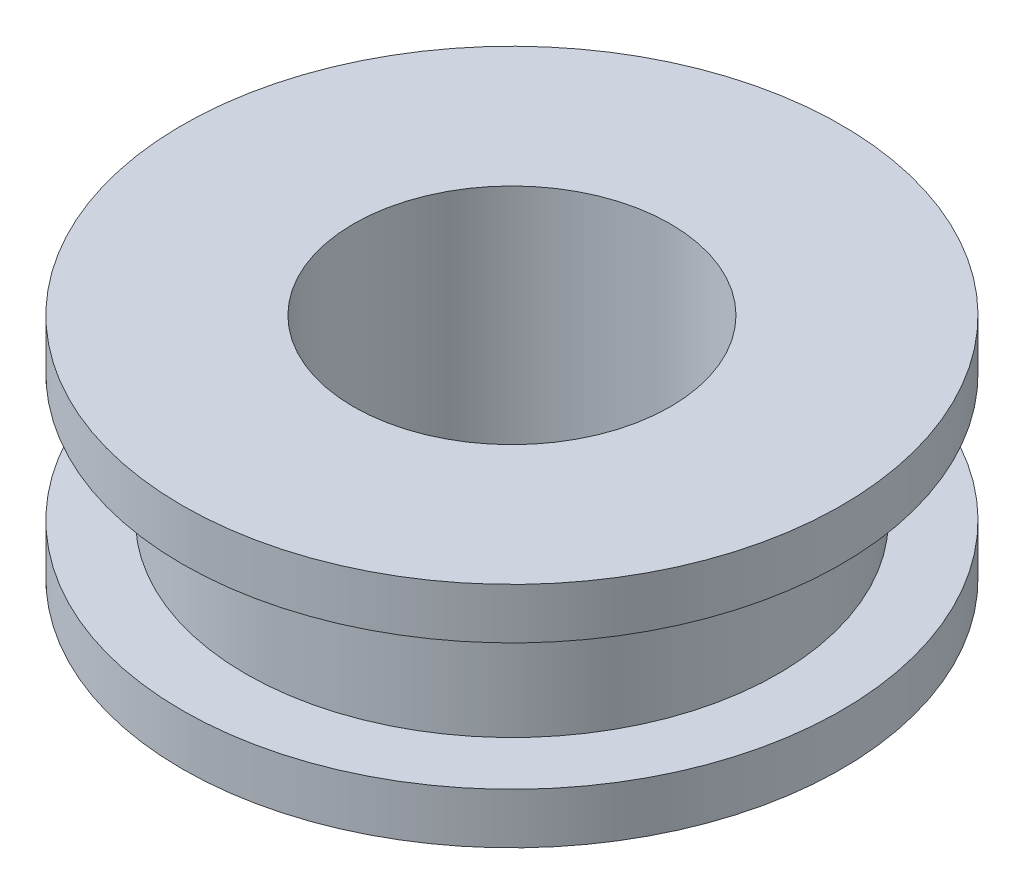
SolidWorks part; units mm, degrees
ref_plane "Front Plane" through (0, 0, 0) normal (0, 0, 1) x (1, 0, 0)
ref_plane "Top Plane" through (0, 0, 0) normal (0, 1, 0) x (1, 0, 0)
ref_plane "Right Plane" through (0, 0, 0) normal (1, 0, 0) x (0, 0, -1)
sketch "Sketch1" plane through (0, 0, 0) normal (0, 0, 1) x (1, 0, 0)
  line L0 (0, 44.3946) -> (0, -64.9116) construction
  line L1 (0, 18) -> (52, 18)
  line L2 (52, 18) -> (52, 10)
  line L3 (52, 10) -> (42, 10)
  line L4 (42, 10) -> (42, -10)
  line L5 (42, -10) -> (52, -10)
  line L6 (52, -10) -> (52, -18)
  line L7 (52, -18) -> (0, -18)
  line L8 (0, -18) -> (0, 18)
  line L9 (25, 18) -> (25, -18)
  point P5 (42, 0)
  dimension "D1" = 52
  dimension "D2" = 8
  dimension "D3" = 36
  dimension "D4" = 42
  dimension "D5" = 25
revolve "Revolve1" add sketch "Sketch1" angle 360 about L0
